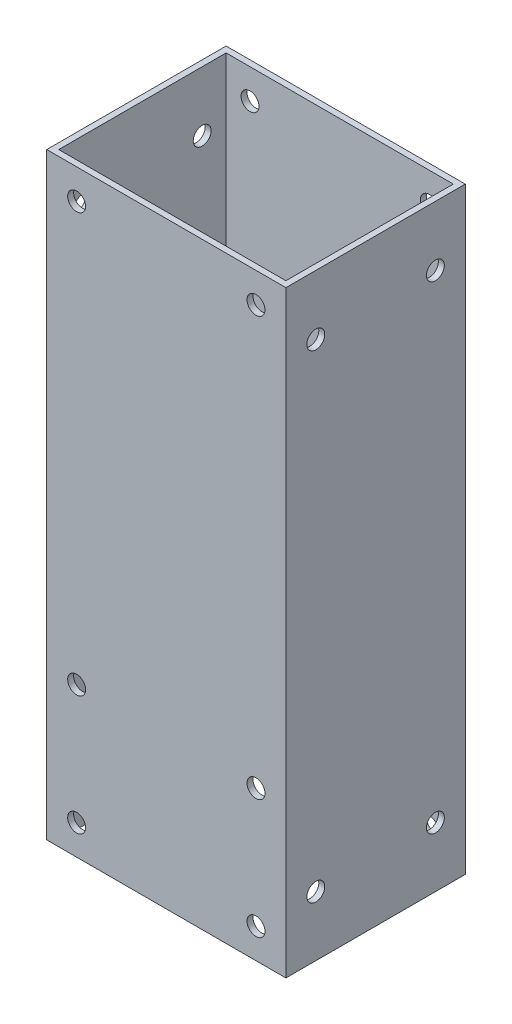
SolidWorks part; units mm, degrees
ref_plane "前视基准面" through (0, 0, 0) normal (0, 0, 1) x (1, 0, 0)
ref_plane "上视基准面" through (0, 0, 0) normal (0, 1, 0) x (1, 0, 0)
ref_plane "右视基准面" through (0, 0, 0) normal (1, 0, 0) x (0, 0, -1)
sketch "草图1" plane through (0, 0, 0) normal (0, 1, 0) x (1, 0, 0)
  line L1 (0, 0) -> (40, 0)
  line L2 (0, 0) -> (0, 30)
  line L3 (0, 30) -> (40, 30)
  line L4 (40, 0) -> (40, 30)
  dimension "D1" = 30
  dimension "D2" = 40
extrude "拉伸-薄壁1" add sketch "草图1" along normal blind 100 thin thin type one direction reverse wall 1
sketch "草图2" plane through (0, 0, 0) normal (0, 0, 1) x (1, 0, 0)
  line L0 (0, 100) -> (0, 0) construction
  line L1 (5, 95) -> (35, 95) construction
  line L2 (5, 95) -> (5, 25) construction
  line L3 (5, 25) -> (35, 25) construction
  line L4 (35, 95) -> (35, 25) construction
  line L5 (40, 100) -> (40, 0) construction
  line L7 (0, 100) -> (40, 100) construction
  line L8 (5, 25) -> (5, 5) construction
  line L9 (5, 5) -> (35, 5) construction
  line L10 (35, 5) -> (35, 25) construction
  line L11 (0, 0) -> (40, 0) construction
  circle A0 centre (5, 95) radius 1.5
  circle A1 centre (35, 95) radius 1.5
  circle A2 centre (35, 25) radius 1.5
  circle A3 centre (5, 25) radius 1.5
  circle A4 centre (5, 5) radius 1.5
  circle A5 centre (35, 5) radius 1.5
  dimension "D1" = 70
  dimension "D5" = 3
  dimension "D2" = 5
  dimension "D3" = 5
  dimension "D4" = 5
  dimension "D6" = 5
extrude "切除-拉伸1" cut sketch "草图2" against normal through all
sketch "草图3" plane through (0, 0, 0) normal (-1, 0, 0) x (0, 0, 1)
  line L0 (-30, 0) -> (0, 0) construction
  line L1 (-25, 90) -> (-5, 90) construction
  line L2 (-25, 90) -> (-25, 10) construction
  line L3 (-25, 10) -> (-5, 10) construction
  line L4 (-5, 90) -> (-5, 10) construction
  line L5 (-30, 100) -> (-30, 0) construction
  line L6 (0, 100) -> (0, 0) construction
  circle A0 centre (-25, 90) radius 1.5
  circle A1 centre (-5, 90) radius 1.5
  circle A2 centre (-25, 10) radius 1.5
  circle A3 centre (-5, 10) radius 1.5
  dimension "D5" = 3
  dimension "D1" = 80
  dimension "D2" = 10
  dimension "D3" = 5
  dimension "D4" = 5
extrude "切除-拉伸2" cut sketch "草图3" against normal through all
